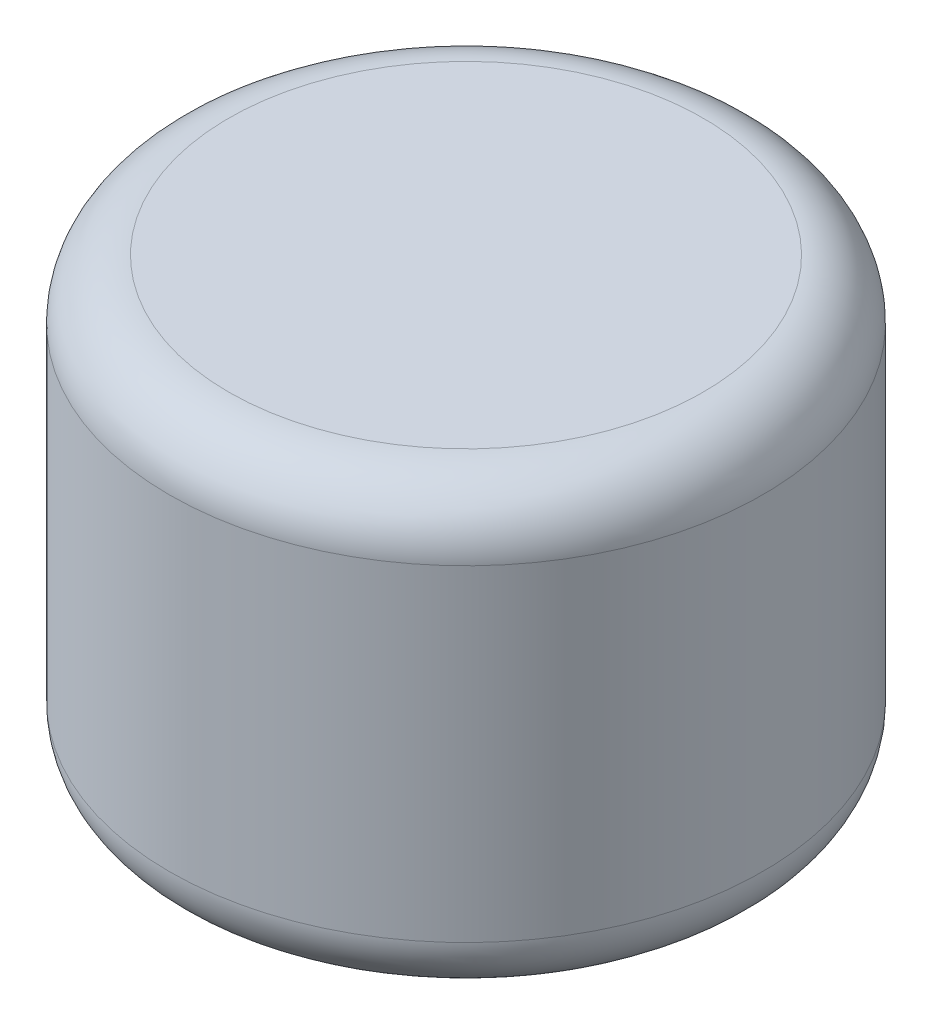
SolidWorks part; units mm, degrees
ref_plane "Front Plane" through (0, 0, 0) normal (0, 0, 1) x (1, 0, 0)
ref_plane "Top Plane" through (0, 0, 0) normal (0, 1, 0) x (1, 0, 0)
ref_plane "Right Plane" through (0, 0, 0) normal (1, 0, 0) x (0, 0, -1)
sketch "Sketch3" plane through (0, 0, 0) normal (0, 1, 0) x (1, 0, 0)
  circle A0 centre (0, 0) radius 2
  dimension "D1" = 4
extrude "Boss-Extrude2" add sketch "Sketch3" along normal mid plane 3
fillet "Fillet1" radius 0.4 2 edges at (0, -1.5, 2) (0, 1.5, 2)
